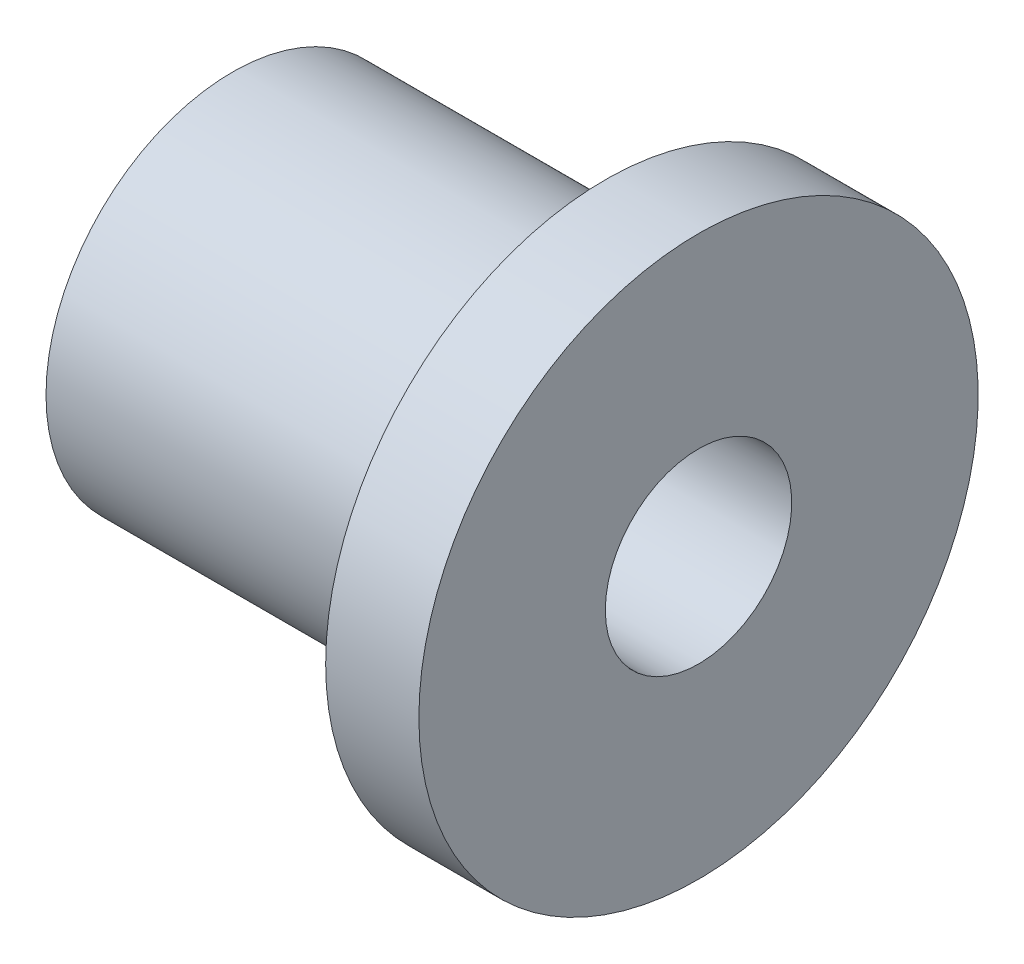
SolidWorks part; units mm, degrees
ref_plane "Front Plane" through (0, 0, 0) normal (0, 0, 1) x (1, 0, 0)
ref_plane "Top Plane" through (0, 0, 0) normal (0, 1, 0) x (1, 0, 0)
ref_plane "Right Plane" through (0, 0, 0) normal (1, 0, 0) x (0, 0, -1)
sketch "Sketch1" plane through (0, 0, 0) normal (0, 0, 1) x (1, 0, 0)
  line L0 (0, 3.175) -> (0, 6.35)
  line L1 (0, 6.35) -> (12.7, 6.35)
  line L2 (12.7, 6.35) -> (12.7, 9.525)
  line L3 (12.7, 9.525) -> (15.875, 9.525)
  line L4 (15.875, 9.525) -> (15.875, 3.175)
  line L5 (15.875, 3.175) -> (0, 3.175)
  line L6 (0, 0) -> (36.0885, 0) construction
  dimension "D1" = 6.35
  dimension "D2" = 6.35
  dimension "D3" = 3.175
  dimension "D4" = 12.7
  dimension "D5" = 9.525
revolve "Revolve1" add sketch "Sketch1" angle 360 about L6
